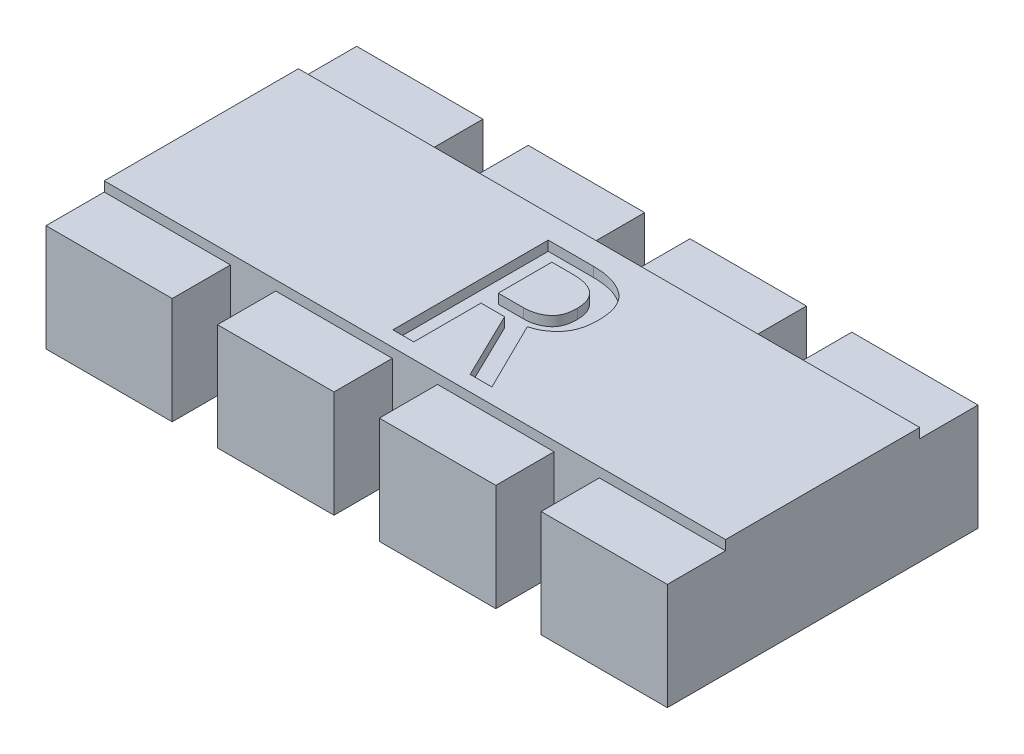
SolidWorks part; units mm, degrees
ref_plane "前视基准面" through (0, 0, 0) normal (0, 0, 1) x (1, 0, 0)
ref_plane "上视基准面" through (0, 0, 0) normal (0, 1, 0) x (1, 0, 0)
ref_plane "右视基准面" through (0, 0, 0) normal (1, 0, 0) x (0, 0, -1)
sketch "草图1" plane through (0, 0, 0) normal (0, 1, 0) x (1, 0, 0)
  line L0 (0, 1.6) -> (0.65, 1.6)
  line L1 (3.5204, 0.8) -> (-0.9254, 0.8) construction
  line L2 (0, 0) -> (0, 1.6)
  line L3 (0.65, 1.6) -> (0.65, 1.3)
  line L4 (3.2, 0) -> (3.2, 1.6)
  line L5 (0.65, 1.3) -> (0.8833, 1.3)
  line L6 (0.8833, 1.3) -> (0.8833, 1.6)
  line L7 (0.8833, 1.6) -> (1.4833, 1.6)
  line L8 (1.4833, 1.6) -> (1.4833, 1.3)
  line L9 (1.4833, 1.3) -> (1.7167, 1.3)
  line L10 (1.7167, 1.3) -> (1.7167, 1.6)
  line L11 (1.7167, 1.6) -> (2.3167, 1.6)
  line L12 (2.3167, 1.6) -> (2.3167, 1.3)
  line L13 (2.3167, 1.3) -> (2.55, 1.3)
  line L14 (2.55, 1.3) -> (2.55, 1.6)
  line L15 (2.55, 1.6) -> (3.2, 1.6)
  line L16 (2.55, 0) -> (3.2, 0)
  line L17 (2.55, 0.3) -> (2.55, 0)
  line L18 (2.3167, 0.3) -> (2.55, 0.3)
  line L19 (2.3167, 0) -> (2.3167, 0.3)
  line L20 (1.7167, 0) -> (2.3167, 0)
  line L21 (1.7167, 0.3) -> (1.7167, 0)
  line L22 (1.4833, 0.3) -> (1.7167, 0.3)
  line L23 (1.4833, 0) -> (1.4833, 0.3)
  line L24 (0.8833, 0) -> (1.4833, 0)
  line L25 (0.8833, 0.3) -> (0.8833, 0)
  line L26 (0.65, 0.3) -> (0.8833, 0.3)
  line L27 (0.65, 0) -> (0.65, 0.3)
  line L28 (0, 0) -> (0.65, 0)
  dimension "D1" = 3.2
  dimension "D2" = 1.6
  dimension "D3" = 0.65
  dimension "D4" = 0.6
  dimension "D5" = 0.3
extrude "凸台-拉伸1" add sketch "草图1" along normal blind 0.55
sketch "草图2" plane through (0, 0.55, 0) normal (0, 1, 0) x (1, 0, 0)
  line L0 (0.8833, 1.3) -> (0.65, 1.3) construction
  line L1 (0, 1.3) -> (3.2, 1.3)
  line L2 (0, 1.3) -> (0, 0.3)
  line L3 (0, 0.3) -> (3.2, 0.3)
  line L4 (3.2, 1.3) -> (3.2, 0.3)
  line L5 (0.65, 0.3) -> (0.8833, 0.3) construction
  line L8 (3.2, 0) -> (3.2, 1.6) construction
  line L9 (0, 1.6) -> (0, 0) construction
extrude "凸台-拉伸2" add sketch "草图2" along normal blind 0.05
sketch "草图3" plane through (0, 0.6, 0) normal (0, 1, 0) x (1, 0, 0)
  text T0 "R" font "黑体" height 0.8
extrude "切除-拉伸1" cut sketch "草图3" against normal blind 0.05
